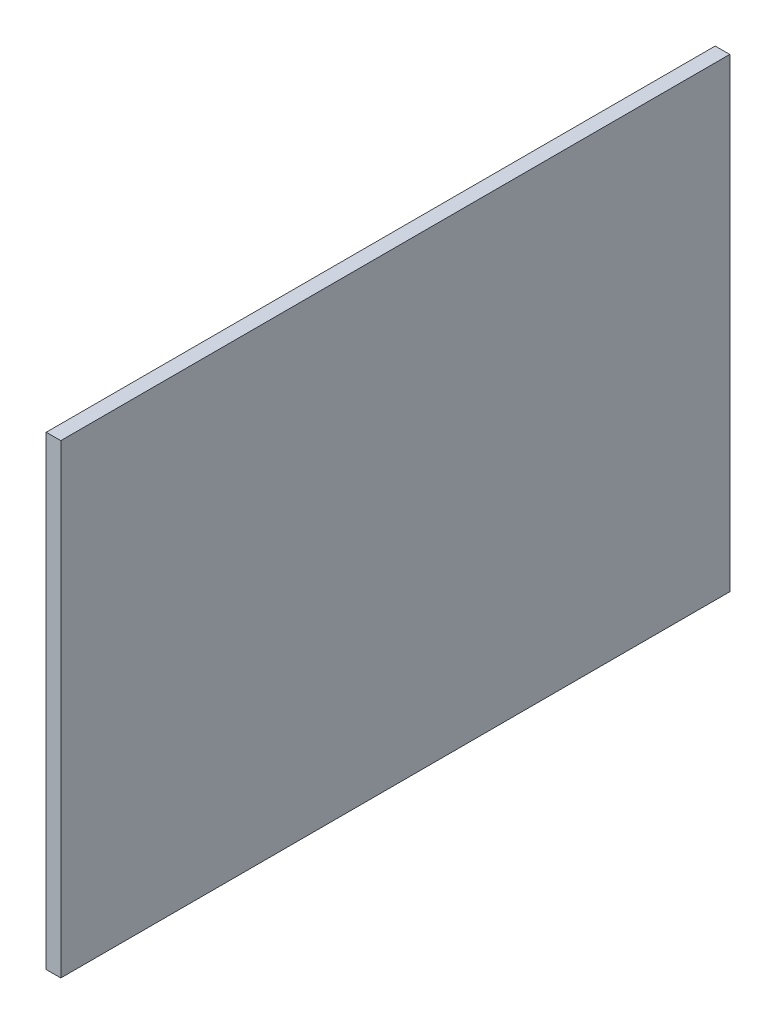
SolidWorks part; units mm, degrees
ref_plane "Front Plane" through (0, 0, 0) normal (0, 0, 1) x (1, 0, 0)
ref_plane "Top Plane" through (0, 0, 0) normal (0, 1, 0) x (1, 0, 0)
ref_plane "Right Plane" through (0, 0, 0) normal (1, 0, 0) x (0, 0, -1)
sketch "Sketch1" plane through (0, 0, 0) normal (1, 0, 0) x (0, 0, -1)
  line L1 (-74.9413, 57.9578) -> (71.1087, 57.9578)
  line L2 (-74.9413, 57.9578) -> (-74.9413, -43.6422)
  line L3 (-74.9413, -43.6422) -> (71.1087, -43.6422)
  line L4 (71.1087, 57.9578) -> (71.1087, -43.6422)
  dimension "D1" = 101.6
  dimension "D2" = 146.05
extrude "Boss-Extrude1" add sketch "Sketch1" along normal blind 3.175
